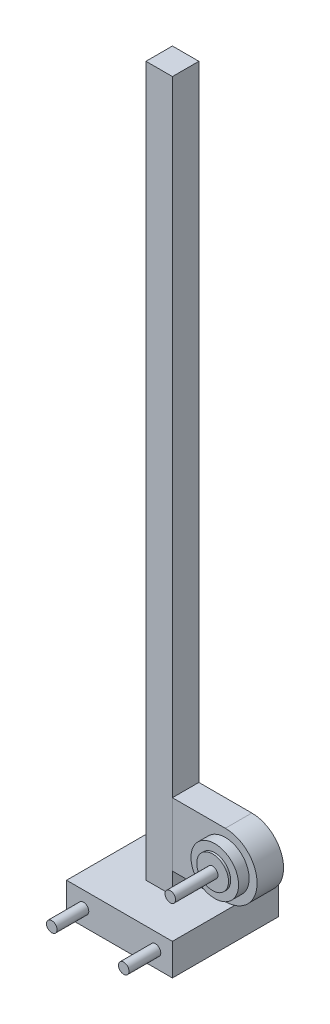
SolidWorks part; units mm, degrees
ref_plane "前视基准面" through (0, 0, 0) normal (0, 0, 1) x (1, 0, 0)
ref_plane "上视基准面" through (0, 0, 0) normal (0, 1, 0) x (1, 0, 0)
ref_plane "右视基准面" through (0, 0, 0) normal (1, 0, 0) x (0, 0, -1)
sketch "草图1" plane through (0, 0, 0) normal (0, 1, 0) x (1, 0, 0)
  line L0 (0, 0) -> (25, 0)
  line L1 (25, 0) -> (25, 25)
  line L2 (25, 25) -> (0, 25)
  line L3 (0, 25) -> (0, 0)
  dimension "D1" = 25
  dimension "D2" = 25
extrude "凸台-拉伸1" add sketch "草图1" along normal blind 700
sketch "草图2" plane through (0, 0, 0) normal (0, 0, 1) x (1, 0, 0)
  line L0 (75, 110) -> (25, 110)
  line L1 (25, 700) -> (25, 0) construction
  line L2 (25, 110) -> (25, 50)
  line L3 (25, 50) -> (75, 50)
  line L4 (0, 0) -> (25, 0) construction
  arc A0 (75, 50) -> (75, 110) centre (75, 80) ccw
  dimension "D2" = 60
  dimension "D1" = 50
  dimension "D3" = 50
extrude "凸台-拉伸2" add sketch "草图2" against normal up to surface (25 mm away) separate body up to face at (12.5, 350, -25)
sketch "草图3" plane through (0, 0, 0) normal (0, 0, 1) x (1, 0, 0)
  circle A0 centre (75, 80) radius 22.5
  dimension "D1" = 45
extrude "凸台-拉伸3" add sketch "草图3" along normal blind 10 separate body
sketch "草图4" plane through (0, 0, 10) normal (0, 0, 1) x (1, 0, 0)
  circle A0 centre (75, 80) radius 15
  dimension "D1" = 30
extrude "凸台-拉伸4" add sketch "草图4" along normal blind 2 separate body
sketch "草图6" plane through (0, 0, 12) normal (0, 0, 1) x (1, 0, 0)
  circle A0 centre (75, 80) radius 5
  dimension "D1" = 10
extrude "凸台-拉伸5" add sketch "草图6" along normal blind 40 separate body
sketch "草图7" plane through (0, 0, 0) normal (0, 1, 0) x (1, 0, 0)
  line L0 (-37.5, -37.5) -> (62.5, -37.5)
  line L1 (62.5, -37.5) -> (62.5, 62.5)
  line L2 (62.5, 62.5) -> (-37.5, 62.5)
  line L3 (-37.5, 62.5) -> (-37.5, -37.5)
  line L4 (0, 0) -> (25, 0) construction
  line L5 (0, 25) -> (0, 0) construction
  dimension "D1" = 100
  dimension "D2" = 100
  dimension "D3" = 37.5
  dimension "D4" = 37.5
extrude "凸台-拉伸6" add sketch "草图7" along normal blind 30
sketch "草图9" plane through (0, 0, 37.5) normal (0, 0, 1) x (1, 0, 0)
  line L0 (12.5, 30) -> (12.5, 0) construction
  line L1 (0, 30) -> (25, 30) construction
  line L2 (-37.5, 0) -> (62.5, 0) construction
  line L3 (-37.5, 15) -> (62.5, 15) construction
  line L4 (-37.5, 30) -> (-37.5, 0) construction
  line L5 (62.5, 30) -> (62.5, 0) construction
  circle A0 centre (-21.5, 15) radius 5
  circle A1 centre (46.5, 15) radius 5
  dimension "D1" = 10
  dimension "D2" = 10
  dimension "D3" = 34
  dimension "D4" = 34
extrude "凸台-拉伸7" add sketch "草图9" along normal blind 30
